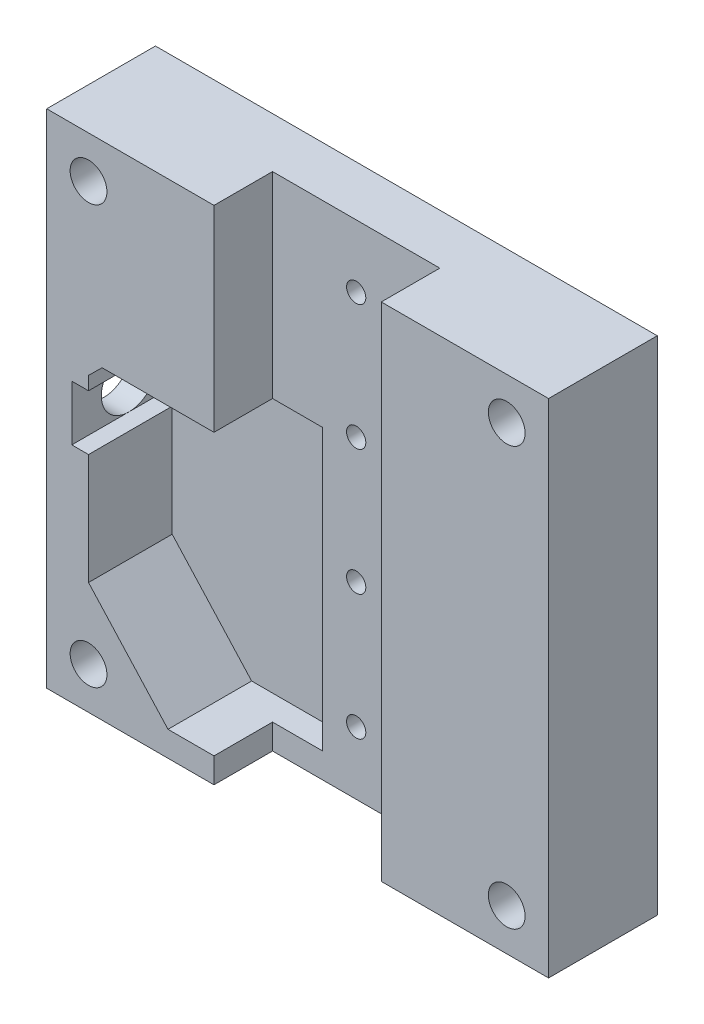
SolidWorks part; units mm, degrees
ref_plane "Front Plane" through (0, 0, 0) normal (0, 0, 1) x (1, 0, 0)
ref_plane "Top Plane" through (0, 0, 0) normal (0, 1, 0) x (1, 0, 0)
ref_plane "Right Plane" through (0, 0, 0) normal (1, 0, 0) x (0, 0, -1)
sketch "Sketch1" plane through (0, 0, 0) normal (0, 0, 1) x (1, 0, 0)
  line L1 (-30, 30) -> (30, 30)
  line L2 (-30, 30) -> (-30, -30)
  line L3 (-30, -30) -> (30, -30)
  line L4 (30, 30) -> (30, -30)
  line L5 (-30, 30) -> (30, -30) construction
  line L6 (-30, -30) -> (30, 30) construction
  point P0 (0, 0)
  dimension "D1" = 60
  dimension "D2" = 60
extrude "Boss-Extrude1" add sketch "Sketch1" along normal blind 6
sketch "Sketch2" plane through (0, 0, 0) normal (0, 0, -1) x (-1, 0, 0)
  line L0 (0, -30) -> (0, 30)
  line L1 (30, -30) -> (-30, -30) construction
  line L2 (-30, 30) -> (30, 30) construction
  circle A0 centre (0, 22.5) radius 1.15
  circle A4 centre (0, -22.5) radius 1.15
  circle A5 centre (0, -7.5) radius 1.15
  circle A6 centre (0, 7.5) radius 1.15
  dimension "D1" = 2.3
  dimension "D2" = 15
  dimension "D3" = 15
  dimension "D4" = 15
sketch "Sketch3" plane through (0, 0, 0) normal (0, 0, -1) x (-1, 0, 0)
  line L7 (2.1, 6.2876) -> (2.1, 8.7124)
  line L8 (2.1, 8.7124) -> (0, 9.9249)
  line L9 (0, 9.9249) -> (-2.1, 8.7124)
  line L10 (-2.1, 8.7124) -> (-2.1, 6.2876)
  line L11 (-2.1, 6.2876) -> (0, 5.0751)
  line L12 (0, 5.0751) -> (2.1, 6.2876)
  line L13 (2.1, -8.7124) -> (2.1, -6.2876)
  line L14 (2.1, -6.2876) -> (0, -5.0751)
  line L15 (0, -5.0751) -> (-2.1, -6.2876)
  line L16 (-2.1, -6.2876) -> (-2.1, -8.7124)
  line L17 (-2.1, -8.7124) -> (0, -9.9249)
  line L18 (0, -9.9249) -> (2.1, -8.7124)
  line L19 (2.1, -23.7124) -> (2.1, -21.2876)
  line L20 (2.1, -21.2876) -> (0, -20.0751)
  line L21 (0, -20.0751) -> (-2.1, -21.2876)
  line L22 (-2.1, -21.2876) -> (-2.1, -23.7124)
  line L23 (-2.1, -23.7124) -> (0, -24.9249)
  line L24 (0, -24.9249) -> (2.1, -23.7124)
  line L27 (0, 20.0751) -> (2.1, 21.2876)
  line L28 (2.1, 21.2876) -> (2.1, 23.7124)
  line L29 (2.1, 23.7124) -> (0, 24.9249)
  line L30 (0, 24.9249) -> (-2.1, 23.7124)
  line L31 (-2.1, 23.7124) -> (-2.1, 21.2876)
  line L32 (-2.1, 21.2876) -> (0, 20.0751)
  circle A0 centre (0, 22.5) radius 2.1 construction
  circle A1 centre (0, 7.5) radius 2.1 construction
  circle A2 centre (0, -7.5) radius 2.1 construction
  circle A3 centre (0, -22.5) radius 2.1 construction
extrude "Cut-Extrude2" cut sketch "Sketch3" against normal blind 3
sketch "Sketch12" plane through (0, 0, 0) normal (0, 0, -1) x (-1, 0, 0)
  circle A0 centre (0, 22.5) radius 1.15
  circle A1 centre (0, 7.5) radius 1.15
  circle A2 centre (0, -7.5) radius 1.15
  circle A3 centre (0, -22.5) radius 1.15
extrude "Cut-Extrude9" cut sketch "Sketch12" against normal through all
sketch "Sketch4" plane through (0, 0, 6) normal (0, 0, 1) x (1, 0, 0)
  line L0 (0, -30) -> (-4, -30)
  line L1 (-30, -30) -> (30, -30) construction
  line L2 (-4, -30) -> (-4, -27)
  line L5 (30, 30) -> (-30, 30) construction
  line L6 (-4, 30) -> (-4, 6.5)
  dimension "D1" = 4
  dimension "D2" = 3
sketch "Sketch5" plane through (0, 0, 6) normal (0, 0, 1) x (1, 0, 0)
  line L3 (-30, -30) -> (30, -30) construction
  line L4 (-10, 30) -> (10, 30)
  line L5 (-10, 30) -> (-10, -30)
  line L6 (-10, -30) -> (10, -30)
  line L7 (10, 30) -> (10, -30)
  line L8 (-10, 30) -> (10, -30) construction
  line L9 (-10, -30) -> (10, 30) construction
  line L11 (-30, 30) -> (30, 30)
  line L12 (-30, 30) -> (-30, -30)
  line L13 (-30, -30) -> (30, -30)
  line L14 (30, 30) -> (30, -30)
  line L15 (-30, 30) -> (30, -30) construction
  line L16 (-30, -30) -> (30, 30) construction
  point P6 (0, 0)
  point P14 (0, 0)
  line M5 (30, -30) -> (30, 30)
  line M6 (30, 30) -> (-30, 30)
  line M7 (-30, 30) -> (-30, -30)
  line M8 (-30, -30) -> (30, -30)
extrude "Boss-Extrude2" add sketch "Sketch5" along normal blind 7 contours L5 M6 M7 M8 | L7 M6 M8 M5
sketch "Sketch6" plane through (0, 0, 13) normal (0, 0, 1) x (1, 0, 0)
  line L2 (-20, -20) -> (20, -20)
  line L3 (-20, -20) -> (-20, 20)
  line L4 (-20, 20) -> (20, 20)
  line L5 (20, -20) -> (20, 20)
  line L6 (-20, -20) -> (20, 20) construction
  line L7 (-20, 20) -> (20, -20) construction
  line L8 (20, -20) -> (30, -20)
  line L9 (20, -20) -> (20, -30)
  line L10 (20, -30) -> (30, -30)
  line L11 (30, -20) -> (30, -30)
  line L12 (-20, -20) -> (-30, -20)
  line L13 (-20, -20) -> (-20, -30)
  line L14 (-20, -30) -> (-30, -30)
  line L15 (-30, -20) -> (-30, -30)
  line L16 (-20, 20) -> (-20, 30)
  line L17 (-20, 20) -> (-30, 20)
  line L18 (-30, 20) -> (-30, 30)
  line L19 (-20, 30) -> (-30, 30)
  line L20 (20, 20) -> (30, 20)
  line L21 (20, 20) -> (20, 30)
  line L22 (20, 30) -> (30, 30)
  line L23 (30, 20) -> (30, 30)
  circle A0 centre (25, -25) radius 2.2
  circle A1 centre (25, -25) radius 1.15
  circle A2 centre (-25, -25) radius 2.2
  circle A3 centre (-25, -25) radius 1.15
  circle A4 centre (-25, 25) radius 2.2
  circle A5 centre (-25, 25) radius 1.15
  circle A6 centre (25, 25) radius 2.2
  circle A7 centre (25, 25) radius 1.15
  point P4 (0, 0)
  point P39 (0, 0)
  dimension "D3" = 4
  dimension "D1" = 40
  dimension "D2" = 40
extrude "Cut-Extrude4" cut sketch "Sketch6" against normal through all contours A5 | A7 | A1 | A3
sketch "Sketch8" plane through (0, 0, 13) normal (0, 0, 1) x (1, 0, 0)
  line L1 (0, 0) -> (15.2626, 15.2626)
  circle A0 centre (-25, 25) radius 2.2
  circle A1 centre (25, 25) radius 2.2
  circle A2 centre (25, -25) radius 2.2
  circle A3 centre (-25, -25) radius 2.2
  point P15 (0, 0)
  circle M2 centre (-25, -25) radius 1.15
  circle M3 centre (-25, 25) radius 1.15
  dimension "D1" = 4
extrude "Cut-Extrude5" cut sketch "Sketch8" against normal blind 9 contours A0 M3 | A1 | A2 | A3 M2
sketch "Sketch9" plane through (0, 0, 13) normal (0, 0, 1) x (1, 0, 0)
  line L0 (-10, -30) -> (-10, -27)
  line L1 (-10, 30) -> (-10, -30) construction
  line L2 (-30, 30) -> (-30, -30) construction
  line L3 (-20, -20) -> (-30, -20)
  line L4 (-20, -20) -> (-20, -30)
  line L5 (-20, -30) -> (-30, -30)
  line L6 (-30, -20) -> (-30, -30)
  line L7 (-20, -20) -> (-30, -30) construction
  line L8 (-20, -30) -> (-30, -20) construction
  line L9 (-33, 3.3) -> (-27, 3.3)
  line L10 (-33, 3.3) -> (-33, -3.3)
  line L11 (-33, -3.3) -> (-27, -3.3)
  line L12 (-27, 3.3) -> (-27, -3.3)
  line L13 (-33, 3.3) -> (-27, -3.3) construction
  line L14 (-33, -3.3) -> (-27, 3.3) construction
  line L15 (-27, 3.3) -> (-25, 3.3)
  line L16 (-10, 6.5) -> (-27, 6.5)
  line L17 (-10, 6.5) -> (-10, -27)
  line L18 (-10, -27) -> (-27, -27)
  line L19 (-27, 6.5) -> (-27, -27)
  line L20 (-27, -3.3) -> (-25, -3.3)
  line L21 (-25, 3.3) -> (-25, 6.5)
  line L22 (-25, -3.3) -> (-25, -20)
  line L23 (-25, 4.9) -> (-21.75, 4.9)
  line L24 (-22.5, -22.5) -> (-20, -20)
  line L25 (-25, -16.55) -> (-15.5, -27)
  line L29 (-25, 6.5) -> (-24.3375, 6.5)
  line L36 (-23.375, 6.5) -> (-25, 4.9)
  line L37 (-25, 4.9) -> (-25, 3.3)
  line L38 (-27, 3.3) -> (-25, 3.3)
  point P5 (-25, -25)
  point P12 (-30, 0)
  point P30 (-25, 4.9)
  dimension "D1" = 3
  dimension "D2" = 6
  dimension "D3" = 6.6
  dimension "D4" = 2
  dimension "D5" = 2
  dimension "D6" = 3.25
extrude "Cut-Extrude6" cut sketch "Sketch9" against normal blind 10
sketch "Sketch10" plane through (0, 0, 6) normal (0, 0, 1) x (1, 0, 0)
  line L1 (-10, -27) -> (-4, -27)
  line L2 (-10, -27) -> (-10, 6.5)
  line L3 (-10, 6.5) -> (-4, 6.5)
  line L4 (-4, -27) -> (-4, 6.5)
extrude "Cut-Extrude7" cut sketch "Sketch10" against normal blind 3
sketch "Sketch11" plane through (-27, 0, 0) normal (1, 0, 0) x (0, 0, -1)
  line L0 (-3, 3.3) -> (-3, -3.3)
  line L1 (-3, 3.3) -> (-3, -3.3) construction
  circle A0 centre (-6.175, 0) radius 3.3
extrude "Cut-Extrude8" cut sketch "Sketch11" against normal through all contours L0 A0
